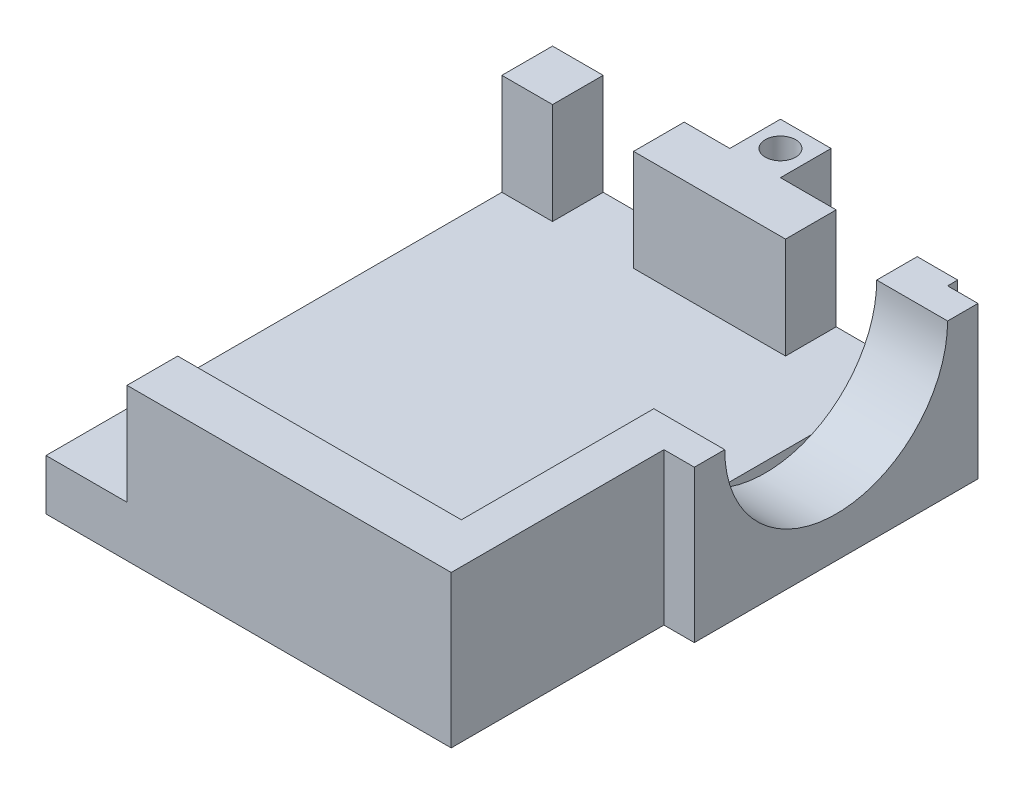
SolidWorks part; units mm, degrees
ref_plane "Front Plane" through (0, 0, 0) normal (0, 0, 1) x (1, 0, 0)
ref_plane "Top Plane" through (0, 0, 0) normal (0, 1, 0) x (1, 0, 0)
ref_plane "Right Plane" through (0, 0, 0) normal (1, 0, 0) x (0, 0, -1)
sketch "Sketch1" plane through (0, 0, 0) normal (0, 1, 0) x (1, 0, 0)
  line L1 (-20, 25) -> (20, 25)
  line L2 (-20, 25) -> (-20, -25)
  line L3 (-20, -25) -> (20, -25)
  line L4 (20, 25) -> (20, -25)
  point P5 (-20, 0)
  point P6 (0, 25)
  dimension "D1" = 40
  dimension "D2" = 50
extrude "Boss-Extrude1" add sketch "Sketch1" along normal blind 5
sketch "Sketch4" plane through (0, 5, 0) normal (0, 1, 0) x (1, 0, 0)
  line L0 (-20, -25) -> (20, -25) construction
  line L1 (20, 25) -> (16, 25)
  line L2 (20, 25) -> (20, -25)
  line L4 (16, 25) -> (16, -20)
  line L5 (20, 25) -> (-20, 25) construction
  line L8 (16, -20) -> (-7, -20)
  line L9 (-7, -25) -> (-7, -20)
  line L10 (-20, 25) -> (-15, 25)
  line L11 (-20, 25) -> (-20, 20)
  line L12 (-20, 20) -> (-15, 20)
  line L13 (-15, 25) -> (-15, 20)
  line L14 (-7, 25) -> (8, 25)
  line L15 (-7, 25) -> (-7, 20)
  line L16 (-7, 20) -> (8, 20)
  line L17 (8, 25) -> (8, 20)
  line L18 (-7, -25) -> (20, -25)
  line L19 (-12, 25) -> (-12, 20) construction
  line L20 (-12, 20) -> (-7, 20) construction
  line L21 (-15, -25) -> (-15, -20) construction
  line L22 (-15, -20) -> (-20, -20) construction
  line L23 (-20, 25) -> (-20, -25) construction
  line L25 (-7, -20) -> (-12, -20)
  line L26 (-7, -20) -> (-7, -25)
  line L27 (-7, -25) -> (-12, -25)
  line L28 (-12, -20) -> (-12, -25)
  line M20 (-20, -25) -> (20, -25)
  line M21 (20, -25) -> (20, 25)
  line M22 (20, 25) -> (-20, 25)
  dimension "D1" = 4
  dimension "D2" = 5
  dimension "D3" = 5
  dimension "D4" = 15
  dimension "D5" = 5
  dimension "D6" = 8
extrude "Boss-Extrude5" add sketch "Sketch4" along normal blind 10 contours L9 L4 L8 M20 M21 M22 | L17 L15 L16 M22 | L11 L10 L13 L12 | L26 L25 L28 L27
sketch "Sketch7" plane through (20, 0, 0) normal (1, 0, 0) x (0, 0, -1)
  line L0 (-25, 15) -> (25, 15) construction
  line L1 (-1, 15) -> (21, 15)
  line L2 (25, 15) -> (25, 0) construction
  arc A0 (-1, 15) -> (21, 15) centre (10, 15) ccw
  dimension "D1" = 22
  dimension "D2" = 15
extrude "Cut-Extrude2" cut sketch "Sketch7" against normal blind 4
sketch "Sketch8" plane through (20, 0, 0) normal (1, 0, 0) x (0, 0, -1)
  line L0 (-1, 15) -> (-4, 15)
  line L1 (-25, 15) -> (-1, 15) construction
  line L2 (-4, 15) -> (-4, 0)
  line L3 (-25, 0) -> (25, 0) construction
  line L4 (-4, 0) -> (24, 0)
  line L5 (24, 0) -> (24, 15)
  line L6 (21, 15) -> (25, 15) construction
  line L7 (24, 15) -> (21, 15)
  line L8 (25, 15) -> (25, 0) construction
  arc A0 (-1, 15) -> (21, 15) centre (10, 15) ccw
  dimension "D2" = 22
  dimension "D1" = 3
  dimension "D3" = 1
extrude "Boss-Extrude7" add sketch "Sketch8" along normal blind 3
sketch "Sketch9" plane through (0, 0, -25) normal (0, 0, -1) x (-1, 0, 0)
  line L0 (-8, 15) -> (7, 15) construction
  line L1 (2.5, 10) -> (-2.5, 10)
  line L2 (2.5, 10) -> (2.5, 15)
  line L3 (2.5, 15) -> (-2.5, 15)
  line L4 (-2.5, 10) -> (-2.5, 15)
  point P6 (0, 10)
  dimension "D1" = 5
  dimension "D2" = 5
extrude "Boss-Extrude8" add sketch "Sketch9" along normal blind 5
sketch "Sketch10" plane through (0, 10, 0) normal (0, -1, 0) x (1, 0, 0)
  line L0 (2.5, -25) -> (-2.5, -25) construction
  line L1 (2.5, -30) -> (2.5, -25) construction
  circle A0 centre (0, -27.5) radius 1.5
  point P4 (0, -25)
  point P7 (2.5, -27.5)
  dimension "D1" = 3
extrude "Cut-Extrude3" cut sketch "Sketch10" against normal blind 5
